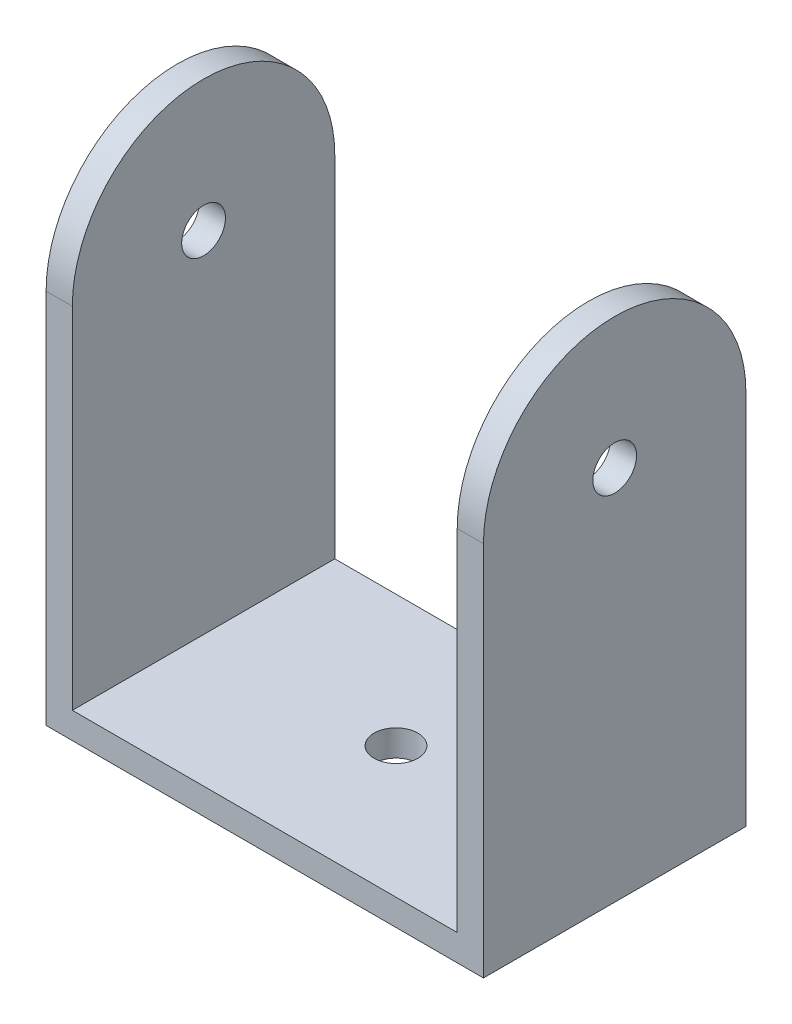
SolidWorks part; units mm, degrees
ref_plane "Front Plane" through (0, 0, 0) normal (0, 0, 1) x (1, 0, 0)
ref_plane "Top Plane" through (0, 0, 0) normal (0, 1, 0) x (1, 0, 0)
ref_plane "Right Plane" through (0, 0, 0) normal (1, 0, 0) x (0, 0, -1)
sketch "Sketch1" plane through (0, 0, 0) normal (0, 1, 0) x (1, 0, 0)
  line L0 (0, 15) -> (0, -15) construction
  line L1 (-25, 15) -> (25, 15)
  line L2 (-25, 15) -> (-25, -15)
  line L3 (-25, -15) -> (25, -15)
  line L4 (25, 15) -> (25, -15)
  dimension "D1" = 50
  dimension "D2" = 30
extrude "Boss-Extrude1" add sketch "Sketch1" along normal blind 3
sketch "Sketch2" plane through (25, 0, 0) normal (1, 0, 0) x (0, 0, -1)
  line L0 (-15, 3) -> (-15, 43)
  line L1 (15, 43) -> (15, 3)
  line L2 (15, 3) -> (-15, 3)
  arc A0 (15, 43) -> (-15, 43) centre (0, 43) ccw
  circle A1 centre (0, 43) radius 2.5
  dimension "D1" = 30
  dimension "D2" = 5
  dimension "D3" = 40
extrude "Boss-Extrude2" add sketch "Sketch2" against normal blind 3
mirror "Mirror1" about plane through (0, 0, 0) normal (1, 0, 0) of "Boss-Extrude2"
sketch "Sketch3" plane through (0, 3, 0) normal (0, 1, 0) x (1, 0, 0)
  circle A0 centre (0, 0) radius 2.5
  dimension "D1" = 5
extrude "Cut-Extrude1" cut sketch "Sketch3" against normal blind 3
